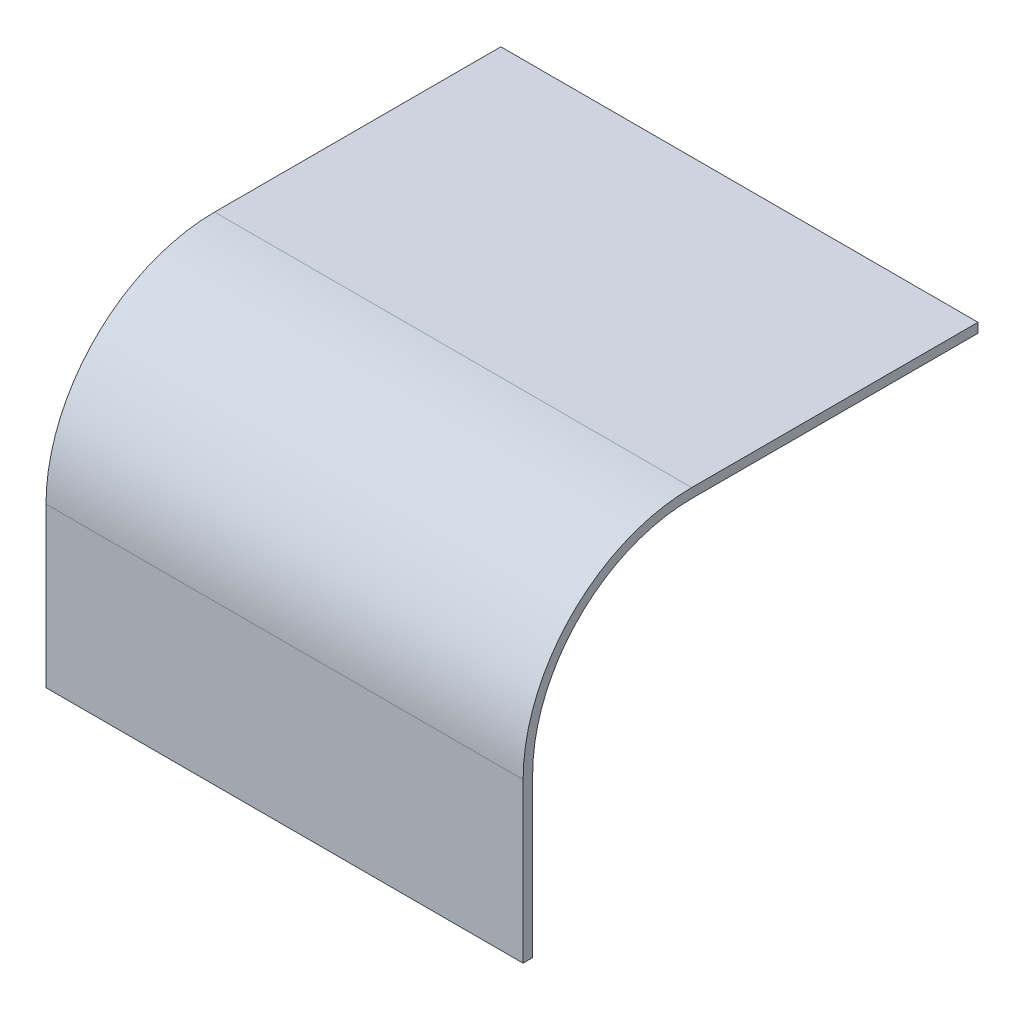
SolidWorks part; units mm, degrees
ref_plane "Alzado" through (0, 0, 0) normal (0, 0, 1) x (1, 0, 0)
ref_plane "Planta" through (0, 0, 0) normal (0, 1, 0) x (1, 0, 0)
ref_plane "Vista lateral" through (0, 0, 0) normal (1, 0, 0) x (0, 0, -1)
sketch "Croquis1" plane through (-7.3057, -32.4567, 940.9263) normal (1, 0, 0) x (0, 0, -1)
  line L0 (-90, 100) -> (0, 100) construction
  line L1 (-140, 0) -> (-140, 50) construction
  line L2 (-90, 100) -> (0, 100)
  line L3 (-140, 0) -> (-140, 50)
  line L4 (-90, 103) -> (0, 103)
  line L5 (-143, 0) -> (-143, 50)
  line L6 (0, 103) -> (0, 100)
  line L7 (-143, 0) -> (-140, 0)
  arc A0 (-90, 100) -> (-140, 50) centre (-90, 50) ccw construction
  arc A1 (-90, 100) -> (-140, 50) centre (-90, 50) ccw
  arc A2 (-90, 103) -> (-143, 50) centre (-90, 50) ccw
  dimension "D1" = 3
extrude "Saliente-Extruir1" add sketch "Croquis1" along normal mid plane 150
